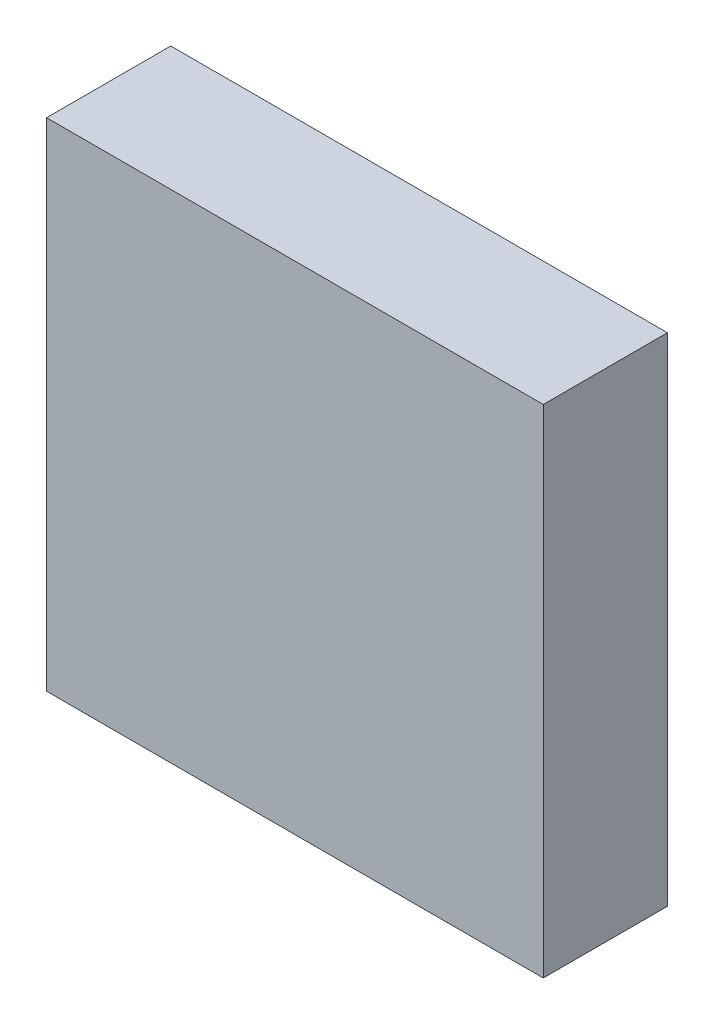
SolidWorks part; units mm, degrees
ref_plane "Front Plane" through (0, 0, 0) normal (0, 0, 1) x (1, 0, 0)
ref_plane "Top Plane" through (0, 0, 0) normal (0, 1, 0) x (1, 0, 0)
ref_plane "Right Plane" through (0, 0, 0) normal (1, 0, 0) x (0, 0, -1)
sketch "Sketch2" plane through (0, 0, 0) normal (0, 0, 1) x (1, 0, 0)
  line L1 (1000, -1000) -> (-1000, -1000)
  line L2 (1000, -1000) -> (1000, 1000)
  line L3 (1000, 1000) -> (-1000, 1000)
  line L4 (-1000, -1000) -> (-1000, 1000)
  line L5 (1000, -1000) -> (-1000, 1000) construction
  line L6 (1000, 1000) -> (-1000, -1000) construction
  point P0 (0, 0)
  dimension "D1" = 2000
  dimension "D2" = 2000
extrude "Boss-Extrude1" add sketch "Sketch2" along normal blind 500
